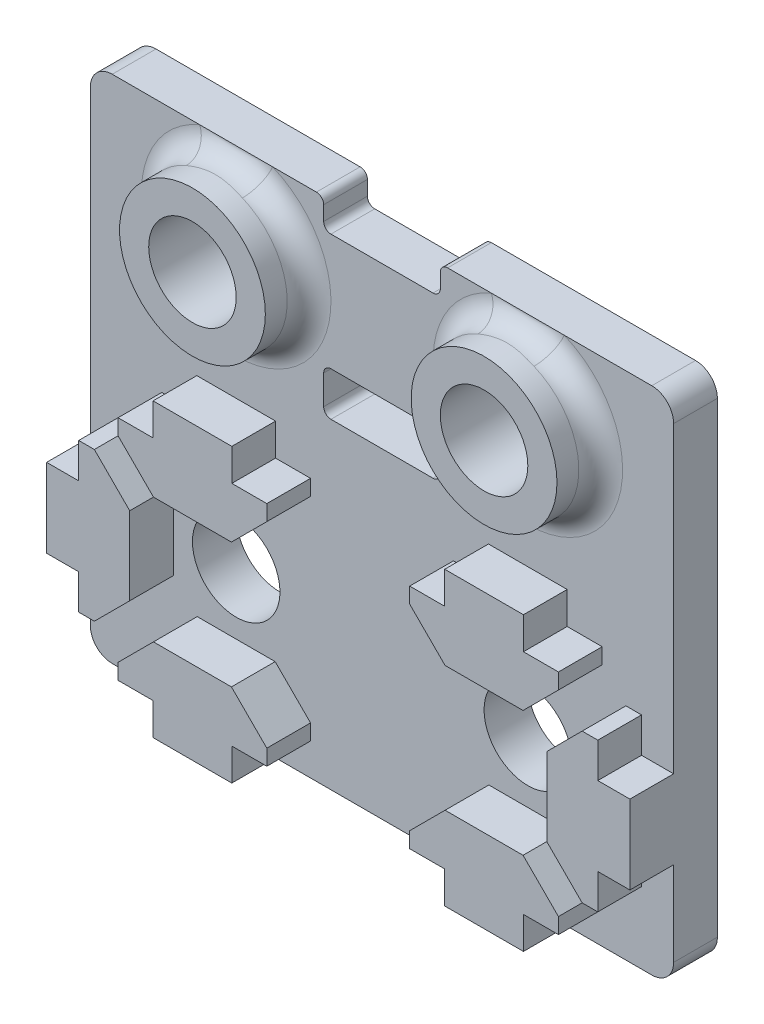
SolidWorks part; units mm, degrees
ref_plane "前视基准面" through (0, 0, 0) normal (0, 0, 1) x (1, 0, 0)
ref_plane "上视基准面" through (0, 0, 0) normal (0, 1, 0) x (1, 0, 0)
ref_plane "右视基准面" through (0, 0, 0) normal (1, 0, 0) x (0, 0, -1)
sketch "草图1" plane through (0, 0, 0) normal (0, 0, 1) x (1, 0, 0)
  line L1 (-20, -10) -> (20, -10)
  line L2 (-20, -10) -> (-20, 10)
  line L3 (-20, 10) -> (20, 10)
  line L4 (20, -10) -> (20, 10)
  line L5 (-20, -10) -> (20, 10) construction
  line L6 (-20, 10) -> (20, -10) construction
  point P0 (0, 0)
extrude "凸台-拉伸1" add sketch "草图1" along normal blind 3
sketch "草图2" plane through (0, 0, 3) normal (0, 0, 1) x (1, 0, 0)
  line L4 (-6.9, 8.2) -> (-6.9, 10)
  line L5 (-13.1, 8.2) -> (-13.1, 10)
  line L6 (-4.5, 6.5607) -> (-4.5, 8.2)
  line L7 (-4.5, 6.5607) -> (-7.1607, 3.9)
  line L9 (-16.5607, 5.5) -> (-18.2, 5.5)
  line L10 (-13.1, 8.2) -> (-15.5, 8.2)
  line L12 (-12.8393, -3.9) -> (-7.1607, -3.9)
  line L13 (-13.9, -2.8393) -> (-13.9, 2.8393)
  line L14 (-12.8393, 3.9) -> (-7.1607, 3.9)
  line L16 (-10, 3.9) -> (-10, -3.9) construction
  line L18 (-6.9, 8.2) -> (-4.5, 8.2)
  line L19 (-16.5607, 5.5) -> (-13.9, 2.8393)
  line L20 (-15.5, 6.5607) -> (-12.8393, 3.9)
  line L21 (-15.5, 6.5607) -> (-15.5, 8.2)
  line L22 (-18.2, 3.1) -> (-18.2, 5.5)
  line L23 (-18.2, 3.1) -> (-20, 3.1)
  line L24 (-18.2, -3.1) -> (-20, -3.1)
  line L25 (-18.2, -3.1) -> (-18.2, -5.5)
  line L26 (-15.5, -6.5607) -> (-15.5, -8.2)
  line L27 (-15.5, -6.5607) -> (-12.8393, -3.9)
  line L28 (-16.5607, -5.5) -> (-13.9, -2.8393)
  line L29 (-6.9, -8.2) -> (-4.5, -8.2)
  line L31 (-13.1, -8.2) -> (-15.5, -8.2)
  line L32 (-16.5607, -5.5) -> (-18.2, -5.5)
  line L34 (-4.5, -6.5607) -> (-7.1607, -3.9)
  line L35 (-4.5, -6.5607) -> (-4.5, -8.2)
  line L36 (-13.1, -8.2) -> (-13.1, -10)
  line L37 (-6.9, -8.2) -> (-6.9, -10)
  line L41 (18.2, 3.1) -> (20, 3.1)
  line L42 (13.1, 8.2) -> (13.1, 10)
  line L43 (6.9, 8.2) -> (6.9, 10)
  line L45 (18.2, 3.1) -> (18.2, 5.5)
  line L46 (15.5, 6.5607) -> (15.5, 8.2)
  line L47 (15.5, 6.5607) -> (12.8393, 3.9)
  line L48 (16.5607, 5.5) -> (13.9, 2.8393)
  line L49 (6.9, 8.2) -> (4.5, 8.2)
  line L51 (7.1607, -3.9) -> (12.8393, -3.9)
  line L53 (7.1607, 3.9) -> (12.8393, 3.9)
  line L54 (13.9, -2.8393) -> (13.9, 2.8393)
  line L55 (13.1, 8.2) -> (15.5, 8.2)
  line L56 (16.5607, 5.5) -> (18.2, 5.5)
  line L58 (4.5, 6.5607) -> (7.1607, 3.9)
  line L59 (4.5, 6.5607) -> (4.5, 8.2)
  line L60 (4.5, -6.5607) -> (4.5, -8.2)
  line L61 (4.5, -6.5607) -> (7.1607, -3.9)
  line L63 (16.5607, -5.5) -> (18.2, -5.5)
  line L64 (13.1, -8.2) -> (15.5, -8.2)
  line L66 (6.9, -8.2) -> (4.5, -8.2)
  line L67 (16.5607, -5.5) -> (13.9, -2.8393)
  line L68 (15.5, -6.5607) -> (12.8393, -3.9)
  line L69 (15.5, -6.5607) -> (15.5, -8.2)
  line L70 (18.2, -3.1) -> (18.2, -5.5)
  line L72 (6.9, -8.2) -> (6.9, -10)
  line L73 (13.1, -8.2) -> (13.1, -10)
  line L74 (18.2, -3.1) -> (20, -3.1)
  line L78 (10, 3.9) -> (10, -3.9) construction
  line L79 (6.1, 0) -> (13.9, 0) construction
  line L86 (13.1, 10) -> (6.9, 10)
  line L87 (20, 3.1) -> (20, -3.1)
  line L88 (13.1, -10) -> (6.9, -10)
  line L89 (-6.9, -10) -> (-13.1, -10)
  line L90 (-20, -3.1) -> (-20, 3.1)
  line L91 (-6.9, 10) -> (-13.1, 10)
  point P0 (-10, 0)
  point P8 (-10, 8.2)
  point P9 (-9.8043, 8.2)
  point P13 (-10, 8.2)
  point P20 (-5, 5)
  point P33 (-15, 5)
  point P50 (-15, -5)
  point P51 (-5, -5)
  point P52 (-10, -8.2)
  point P53 (-9.8043, -8.2)
  point P54 (10, 0)
  point P58 (10, 8.2)
  point P59 (10.1957, 8.2)
  point P63 (10, 8.2)
  point P70 (15, 5)
  point P83 (5, 5)
  point P102 (5, -5)
  point P103 (15, -5)
  point P104 (10, -8.2)
  point P105 (10.1957, -8.2)
extrude "凸台-拉伸2" add sketch "草图2" along normal blind 3
sketch "草图3" plane through (0, 0, 0) normal (0, 0, -1) x (-1, 0, 0)
  circle A0 centre (-10, 0) radius 3
  circle A1 centre (10, 0) radius 3
extrude "切除-拉伸1" cut sketch "草图3" against normal blind 3
sketch "草图4" plane through (0, 0, 0) normal (0, 0, -1) x (-1, 0, 0)
  line L0 (-20, 10) -> (20, 10)
  line L2 (-20, 10) -> (-20, 25)
  line L3 (-20, 25) -> (20, 25)
  line L4 (20, 10) -> (20, 25)
  circle A0 centre (-10, 19) radius 3
  circle A1 centre (10, 19) radius 3
extrude "凸台-拉伸3" add sketch "草图4" against normal blind 3
fillet "圆角3" radius 1.5 4 edges at (20, -10, 1.5) (-20, -10, 1.5) (20, 25, 1.5) (-20, 25, 1.5)
sketch "草图5" plane through (0, 0, 3) normal (0, 0, 1) x (1, 0, 0)
  circle A0 centre (-10, 19) radius 5
  circle A1 centre (10, 19) radius 5
  circle A2 centre (-10, 19) radius 3
  circle A3 centre (10, 19) radius 3
extrude "凸台-拉伸4" add sketch "草图5" along normal blind 3
fillet "圆角4" radius 1.5 2 edges at (5, 19, 3) (-15, 19, 3)
sketch "草图6" plane through (0, 0, 0) normal (0, 0, -1) x (-1, 0, 0)
  line L3 (0, 23.0058) -> (4, 23.0058)
  line L4 (4, 23.0058) -> (4, 25)
  line L5 (18.5, 25) -> (-18.5, 25) construction
  line L6 (4, 25) -> (-4, 25)
  line L7 (-4, 25) -> (-4, 23.0058)
  line L8 (-4, 23.0058) -> (0, 23.0058)
  line L10 (0, 15.0058) -> (-4, 15.0058)
  line L11 (-4, 15.0058) -> (-4, 12.0058)
  line L12 (-4, 12.0058) -> (4, 12.0058)
  line L13 (4, 12.0058) -> (4, 15.0058)
  line L14 (4, 15.0058) -> (0, 15.0058)
extrude "切除-拉伸2" cut sketch "草图6" against normal blind 10
fillet "圆角6" radius 0.5 8 edges at (4, 23.0058, 1.5) (-4, 23.0058, 1.5) (4, 25, 1.5) (-4, 25, 1.5) (4, 15.0058, 1.5) (4, 12.0058, 1.5) (-4, 12.0058, 1.5) (-4, 15.0058, 1.5)
sketch "草图7" plane through (0, 0, 6) normal (0, 0, 1) x (1, 0, 0)
  line L0 (-18.2, -3.1) -> (-18.2, -5.5) construction
  line L1 (-18.2, -5.5) -> (-16.5607, -5.5) construction
  line L2 (-16.5607, -5.5) -> (-13.9, -2.8393) construction
  line L3 (-13.9, -2.8393) -> (-13.9, 2.8393) construction
  line L4 (-13.9, 2.8393) -> (-16.5607, 5.5) construction
  line L5 (-16.5607, 5.5) -> (-18.2, 5.5) construction
  line L6 (-18.2, 5.5) -> (-18.2, 3.1) construction
  line L7 (-18.2, 3.1) -> (-20, 3.1) construction
  line L8 (-20, 3.1) -> (-20, -3.1) construction
  line L9 (-20, -3.1) -> (-18.2, -3.1) construction
  line L10 (-12.8393, -3.9) -> (-15.5, -6.5607) construction
  line L11 (-15.5, -6.5607) -> (-15.5, -8.2) construction
  line L12 (-15.5, -8.2) -> (-13.1, -8.2) construction
  line L13 (-13.1, -8.2) -> (-13.1, -10) construction
  line L14 (-13.1, -10) -> (-6.9, -10) construction
  line L15 (-6.9, -10) -> (-6.9, -8.2) construction
  line L16 (-6.9, -8.2) -> (-4.5, -8.2) construction
  line L17 (-4.5, -8.2) -> (-4.5, -6.5607) construction
  line L18 (-4.5, -6.5607) -> (-7.1607, -3.9) construction
  line L19 (-7.1607, -3.9) -> (-12.8393, -3.9) construction
  line L20 (-4.5, 8.2) -> (-6.9, 8.2) construction
  line L21 (-6.9, 8.2) -> (-6.9, 10) construction
  line L22 (-6.9, 10) -> (-13.1, 10) construction
  line L23 (-13.1, 10) -> (-13.1, 8.2) construction
  line L24 (-13.1, 8.2) -> (-15.5, 8.2) construction
  line L25 (-15.5, 8.2) -> (-15.5, 6.5607) construction
  line L26 (-15.5, 6.5607) -> (-12.8393, 3.9) construction
  line L27 (-12.8393, 3.9) -> (-7.1607, 3.9) construction
  line L28 (-7.1607, 3.9) -> (-4.5, 6.5607) construction
  line L29 (-4.5, 6.5607) -> (-4.5, 8.2) construction
  line L30 (15.5, 8.2) -> (13.1, 8.2) construction
  line L31 (13.1, 8.2) -> (13.1, 10) construction
  line L32 (13.1, 10) -> (6.9, 10) construction
  line L33 (6.9, 10) -> (6.9, 8.2) construction
  line L34 (6.9, 8.2) -> (4.5, 8.2) construction
  line L35 (4.5, 8.2) -> (4.5, 6.5607) construction
  line L36 (4.5, 6.5607) -> (7.1607, 3.9) construction
  line L37 (7.1607, 3.9) -> (12.8393, 3.9) construction
  line L38 (12.8393, 3.9) -> (15.5, 6.5607) construction
  line L39 (15.5, 6.5607) -> (15.5, 8.2) construction
  line L40 (18.2, 3.1) -> (18.2, 5.5) construction
  line L41 (18.2, 5.5) -> (16.5607, 5.5) construction
  line L42 (16.5607, 5.5) -> (13.9, 2.8393) construction
  line L43 (13.9, 2.8393) -> (13.9, -2.8393) construction
  line L44 (13.9, -2.8393) -> (16.5607, -5.5) construction
  line L45 (16.5607, -5.5) -> (18.2, -5.5) construction
  line L46 (18.2, -5.5) -> (18.2, -3.1) construction
  line L47 (18.2, -3.1) -> (20, -3.1) construction
  line L48 (20, -3.1) -> (20, 3.1) construction
  line L49 (20, 3.1) -> (18.2, 3.1) construction
  line L50 (7.1607, -3.9) -> (4.5, -6.5607) construction
  line L51 (4.5, -6.5607) -> (4.5, -8.2) construction
  line L52 (4.5, -8.2) -> (6.9, -8.2) construction
  line L53 (6.9, -8.2) -> (6.9, -10) construction
  line L54 (6.9, -10) -> (13.1, -10) construction
  line L55 (13.1, -10) -> (13.1, -8.2) construction
  line L56 (13.1, -8.2) -> (15.5, -8.2) construction
  line L57 (15.5, -8.2) -> (15.5, -6.5607) construction
  line L58 (15.5, -6.5607) -> (12.8393, -3.9) construction
  line L59 (12.8393, -3.9) -> (7.1607, -3.9) construction
  line L60 (-18.2, -3.1) -> (-18.2, -5.5)
  line L61 (-18.2, -5.5) -> (-16.5607, -5.5)
  line L62 (-16.5607, -5.5) -> (-13.9, -2.8393)
  line L63 (-13.9, -2.8393) -> (-13.9, 2.8393)
  line L64 (-13.9, 2.8393) -> (-16.5607, 5.5)
  line L65 (-16.5607, 5.5) -> (-18.2, 5.5)
  line L66 (-18.2, 5.5) -> (-18.2, 3.1)
  line L67 (-18.2, 3.1) -> (-20, 3.1)
  line L68 (-20, 3.1) -> (-20, 2.7)
  line L69 (-20, -3.1) -> (-18.2, -3.1)
  line L70 (-12.8393, -3.9) -> (-15.5, -6.5607)
  line L71 (-15.5, -6.5607) -> (-15.5, -8.2)
  line L72 (-15.5, -8.2) -> (-13.1, -8.2)
  line L73 (-13.1, -8.2) -> (-13.1, -10)
  line L74 (-13.1, -10) -> (-12.7, -10)
  line L75 (-6.9, -10) -> (-6.9, -8.2)
  line L76 (-6.9, -8.2) -> (-4.5, -8.2)
  line L77 (-4.5, -8.2) -> (-4.5, -6.5607)
  line L78 (-4.5, -6.5607) -> (-7.1607, -3.9)
  line L79 (-7.1607, -3.9) -> (-12.8393, -3.9)
  line L80 (-4.5, 8.2) -> (-6.9, 8.2)
  line L81 (-6.9, 8.2) -> (-6.9, 10)
  line L82 (-6.9, 10) -> (-7.3, 10)
  line L83 (-13.1, 10) -> (-13.1, 8.2)
  line L84 (-13.1, 8.2) -> (-15.5, 8.2)
  line L85 (-15.5, 8.2) -> (-15.5, 6.5607)
  line L86 (-15.5, 6.5607) -> (-12.8393, 3.9)
  line L87 (-12.8393, 3.9) -> (-7.1607, 3.9)
  line L88 (-7.1607, 3.9) -> (-4.5, 6.5607)
  line L89 (-4.5, 6.5607) -> (-4.5, 8.2)
  line L90 (15.5, 8.2) -> (13.1, 8.2)
  line L91 (13.1, 8.2) -> (13.1, 10)
  line L92 (13.1, 10) -> (12.7, 10)
  line L93 (6.9, 10) -> (6.9, 8.2)
  line L94 (6.9, 8.2) -> (4.5, 8.2)
  line L95 (4.5, 8.2) -> (4.5, 6.5607)
  line L96 (4.5, 6.5607) -> (7.1607, 3.9)
  line L97 (7.1607, 3.9) -> (12.8393, 3.9)
  line L98 (12.8393, 3.9) -> (15.5, 6.5607)
  line L99 (15.5, 6.5607) -> (15.5, 8.2)
  line L100 (18.2, 3.1) -> (18.2, 5.5)
  line L101 (18.2, 5.5) -> (16.5607, 5.5)
  line L102 (16.5607, 5.5) -> (13.9, 2.8393)
  line L103 (13.9, 2.8393) -> (13.9, -2.8393)
  line L104 (13.9, -2.8393) -> (16.5607, -5.5)
  line L105 (16.5607, -5.5) -> (18.2, -5.5)
  line L106 (18.2, -5.5) -> (18.2, -3.1)
  line L107 (18.2, -3.1) -> (20, -3.1)
  line L108 (20, -3.1) -> (20, -2.7)
  line L109 (20, 3.1) -> (18.2, 3.1)
  line L110 (7.1607, -3.9) -> (4.5, -6.5607)
  line L111 (4.5, -6.5607) -> (4.5, -8.2)
  line L112 (4.5, -8.2) -> (6.9, -8.2)
  line L113 (6.9, -8.2) -> (6.9, -10)
  line L114 (6.9, -10) -> (7.3, -10)
  line L115 (13.1, -10) -> (13.1, -8.2)
  line L116 (13.1, -8.2) -> (15.5, -8.2)
  line L117 (15.5, -8.2) -> (15.5, -6.5607)
  line L118 (15.5, -6.5607) -> (12.8393, -3.9)
  line L119 (12.8393, -3.9) -> (7.1607, -3.9)
  line L120 (7.3263, -4.3) -> (4.9, -6.7263)
  line L121 (4.9, -6.7263) -> (4.9, -7.8)
  line L122 (4.9, -7.8) -> (7.3, -7.8)
  line L123 (7.3, -7.8) -> (7.3, -9.6)
  line L125 (12.7, -9.6) -> (12.7, -7.8)
  line L126 (12.7, -7.8) -> (15.1, -7.8)
  line L127 (15.1, -7.8) -> (15.1, -6.7263)
  line L128 (15.1, -6.7263) -> (12.6737, -4.3)
  line L129 (12.6737, -4.3) -> (7.3263, -4.3)
  line L130 (17.8, 2.7) -> (17.8, 5.1)
  line L131 (17.8, 5.1) -> (16.7263, 5.1)
  line L132 (16.7263, 5.1) -> (14.3, 2.6737)
  line L133 (14.3, 2.6737) -> (14.3, -2.6737)
  line L134 (14.3, -2.6737) -> (16.7263, -5.1)
  line L135 (16.7263, -5.1) -> (17.8, -5.1)
  line L136 (17.8, -5.1) -> (17.8, -2.7)
  line L137 (17.8, -2.7) -> (19.6, -2.7)
  line L139 (19.6, 2.7) -> (17.8, 2.7)
  line L140 (15.1, 7.8) -> (12.7, 7.8)
  line L141 (12.7, 7.8) -> (12.7, 9.6)
  line L143 (7.3, 9.6) -> (7.3, 7.8)
  line L144 (7.3, 7.8) -> (4.9, 7.8)
  line L145 (4.9, 7.8) -> (4.9, 6.7263)
  line L146 (4.9, 6.7263) -> (7.3263, 4.3)
  line L147 (7.3263, 4.3) -> (12.6737, 4.3)
  line L148 (12.6737, 4.3) -> (15.1, 6.7263)
  line L149 (15.1, 6.7263) -> (15.1, 7.8)
  line L150 (-17.8, -2.7) -> (-17.8, -5.1)
  line L151 (-17.8, -5.1) -> (-16.7263, -5.1)
  line L152 (-16.7263, -5.1) -> (-14.3, -2.6737)
  line L153 (-14.3, -2.6737) -> (-14.3, 2.6737)
  line L154 (-14.3, 2.6737) -> (-16.7263, 5.1)
  line L155 (-16.7263, 5.1) -> (-17.8, 5.1)
  line L156 (-17.8, 5.1) -> (-17.8, 2.7)
  line L157 (-17.8, 2.7) -> (-19.6, 2.7)
  line L159 (-19.6, -2.7) -> (-17.8, -2.7)
  line L160 (-12.6737, -4.3) -> (-15.1, -6.7263)
  line L161 (-15.1, -6.7263) -> (-15.1, -7.8)
  line L162 (-15.1, -7.8) -> (-12.7, -7.8)
  line L163 (-12.7, -7.8) -> (-12.7, -9.6)
  line L165 (-7.3, -9.6) -> (-7.3, -7.8)
  line L166 (-7.3, -7.8) -> (-4.9, -7.8)
  line L167 (-4.9, -7.8) -> (-4.9, -6.7263)
  line L168 (-4.9, -6.7263) -> (-7.3263, -4.3)
  line L169 (-7.3263, -4.3) -> (-12.6737, -4.3)
  line L170 (-4.9, 7.8) -> (-7.3, 7.8)
  line L171 (-7.3, 7.8) -> (-7.3, 9.6)
  line L173 (-12.7, 9.6) -> (-12.7, 7.8)
  line L174 (-12.7, 7.8) -> (-15.1, 7.8)
  line L175 (-15.1, 7.8) -> (-15.1, 6.7263)
  line L176 (-15.1, 6.7263) -> (-12.6737, 4.3)
  line L177 (-12.6737, 4.3) -> (-7.3263, 4.3)
  line L178 (-7.3263, 4.3) -> (-4.9, 6.7263)
  line L179 (-4.9, 6.7263) -> (-4.9, 7.8)
  line L180 (-19.6, -2.7) -> (-20, -2.7)
  line L181 (-19.6, 2.7) -> (-20, 2.7)
  line L182 (-7.3, -9.6) -> (-7.3, -10)
  line L183 (-12.7, -9.6) -> (-12.7, -10)
  line L184 (-7.3, 9.6) -> (-7.3, 10)
  line L185 (-12.7, 9.6) -> (-12.7, 10)
  line L186 (-12.7, 10) -> (-13.1, 10)
  line L187 (-20, -2.7) -> (-20, -3.1)
  line L188 (-7.3, 9.6) -> (-12.7, 9.6) construction
  line L189 (-6.9, 10) -> (-13.1, 10) construction
  line L190 (-19.6, 2.7) -> (-19.6, -2.7) construction
  line L191 (-7.3, -10) -> (-6.9, -10)
  line L192 (-20, 3.1) -> (-20, -3.1) construction
  line L193 (-12.7, -9.6) -> (-7.3, -9.6) construction
  line L194 (12.7, -9.6) -> (12.7, -10)
  line L195 (-13.1, -10) -> (-6.9, -10) construction
  line L196 (7.3, -9.6) -> (7.3, -10)
  line L197 (19.6, -2.7) -> (20, -2.7)
  line L198 (19.6, 2.7) -> (20, 2.7)
  line L199 (7.3, 9.6) -> (7.3, 10)
  line L200 (7.3, 10) -> (6.9, 10)
  line L201 (20, 2.7) -> (20, 3.1)
  line L202 (12.7, 9.6) -> (12.7, 10)
  line L203 (13.1, 10) -> (6.9, 10) construction
  line L204 (12.7, -10) -> (13.1, -10)
  line L205 (12.7, 9.6) -> (7.3, 9.6) construction
  line L206 (20, -3.1) -> (20, 3.1) construction
  line L207 (19.6, -2.7) -> (19.6, 2.7) construction
  line L208 (7.3, -9.6) -> (12.7, -9.6) construction
  line L210 (6.9, -10) -> (13.1, -10) construction
  dimension "D1" = 0.4
  dimension "D2" = 0.4
  dimension "D3" = 0.4
  dimension "D4" = 0.4
  dimension "D5" = 0.4
  dimension "D6" = 0.4
extrude "切除-拉伸3" cut sketch "草图7" against normal blind 3
